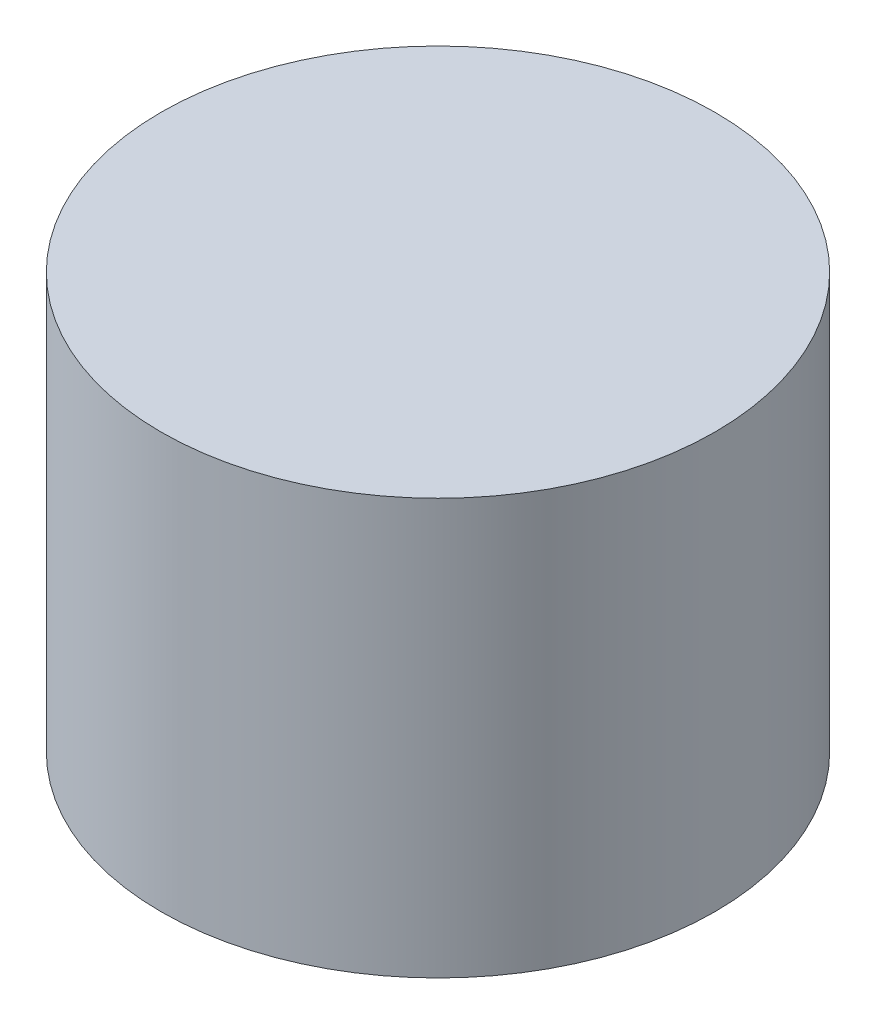
SolidWorks part; units mm, degrees
ref_plane "Front Plane" through (0, 0, 0) normal (0, 0, 1) x (1, 0, 0)
ref_plane "Top Plane" through (0, 0, 0) normal (0, 1, 0) x (1, 0, 0)
ref_plane "Right Plane" through (0, 0, 0) normal (1, 0, 0) x (0, 0, -1)
sketch "Sketch1" plane through (0, 0, 0) normal (0, 1, 0) x (1, 0, 0)
  circle A0 centre (0, 0) radius 10
  dimension "D1" = 20
extrude "Boss-Extrude1" add sketch "Sketch1" along normal blind 15
